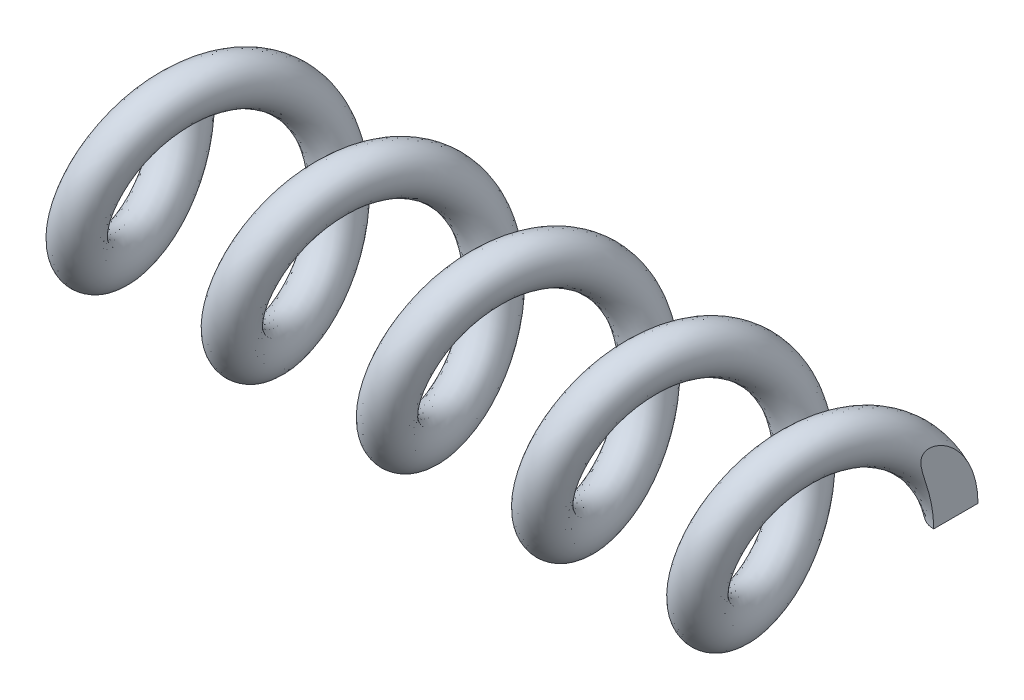
SolidWorks part; units mm, degrees
ref_plane "Front Plane" through (0, 0, 0) normal (0, 0, 1) x (1, 0, 0)
ref_plane "Top Plane" through (0, 0, 0) normal (0, 1, 0) x (1, 0, 0)
ref_plane "Right Plane" through (0, 0, 0) normal (1, 0, 0) x (0, 0, -1)
sketch "Sketch1" plane through (0, 0, 0) normal (1, 0, 0) x (0, 0, -1)
  circle A0 centre (0, 0) radius 4
curve "Helix/Spiral1" pitch 7 height 35 turns 5
sketch "Sketch2" plane through (0, 0, 0) normal (0, 1, 0) x (1, 0, 0)
  line L0 (0, 0) -> (0, 4) construction
  circle A0 centre (0, 4) radius 1
  spline S0 degree 3 poles (261.2112, -1978.3412) (-16.256, -247.6448) (-7.1711, 19.2828) (0.8749, 2.9021) (1.3125, 1.5706) (1.75, 0) (2.1875, -1.5706) (2.625, -2.9021) (3.0625, -3.7917) (3.5, -4.1041) (3.9375, -3.7917) (4.375, -2.9021) (4.8125, -1.5706) (5.25, 0) (5.6875, 1.5706) (6.125, 2.9021) (6.5625, 3.7917) (7, 4.1041) (7.4375, 3.7917) (7.875, 2.9021) (8.3125, 1.5706) (8.75, 0) (9.1875, -1.5706) (9.625, -2.9021) (10.0625, -3.7917) (10.5, -4.1041) (10.9375, -3.7917) (11.375, -2.9021) (11.8125, -1.5706) (12.25, 0) (12.6875, 1.5706) (13.125, 2.9021) (13.5625, 3.7917) (14, 4.1041) (14.4375, 3.7917) (14.875, 2.9021) (15.3125, 1.5706) (15.75, 0) (16.1875, -1.5706) (16.625, -2.9021) (17.0625, -3.7917) (17.5, -4.1041) (17.9375, -3.7917) (18.375, -2.9021) (18.8125, -1.5706) (19.25, 0) (19.6875, 1.5706) (20.125, 2.9021) (20.5625, 3.7917) (21, 4.1041) (21.4375, 3.7917) (21.875, 2.9021) (22.3125, 1.5706) (22.75, 0) (23.1875, -1.5706) (23.625, -2.9021) (24.0625, -3.7917) (24.5, -4.1041) (24.9375, -3.7917) (25.375, -2.9021) (25.8125, -1.5706) (26.25, 0) (26.6875, 1.5706) (27.125, 2.9021) (27.5625, 3.7917) (28, 4.1041) (28.4375, 3.7917) (28.875, 2.9021) (29.3125, 1.5706) (29.75, 0) (30.1875, -1.5706) (30.625, -2.9021) (31.0625, -3.7917) (31.5, -4.1041) (31.9375, -3.7917) (32.375, -2.9021) (32.8125, -1.5706) (33.25, 0) (33.6875, 1.5706) (34.1251, 2.9021) (42.1711, 19.2829) (51.2562, -247.65) (-226.2194, -1978.392) knots -0.652959 -0.652959 -0.652959 -0.652959 0.0125 0.025 0.0375 0.05 0.0625 0.075 0.0875 0.1 0.1125 0.125 0.1375 0.15 0.1625 0.175 0.1875 0.2 0.2125 0.225 0.2375 0.25 0.2625 0.275 0.2875 0.3 0.3125 0.325 0.3375 0.35 0.3625 0.375 0.3875 0.4 0.4125 0.425 0.4375 0.45 0.4625 0.475 0.4875 0.5 0.5125 0.525 0.5375 0.55 0.5625 0.575 0.5875 0.6 0.6125 0.625 0.6375 0.65 0.6625 0.675 0.6875 0.7 0.7125 0.725 0.7375 0.75 0.7625 0.775 0.7875 0.8 0.8125 0.825 0.8375 0.85 0.8625 0.875 0.8875 0.9 0.9125 0.925 0.9375 0.95 0.9625 0.975 0.9875 1.652966 1.652966 1.652966 1.652966 only from (0, 4) to (35, 4) construction
  spline S1 degree 3 poles (0, 4) (0.145, 4) (0.4379, 3.7917) (0.8749, 2.9021) (1.3125, 1.5706) (1.75, 0) (2.1875, -1.5706) (2.625, -2.9021) (3.0625, -3.7917) (3.5, -4.1041) (3.9375, -3.7917) (4.375, -2.9021) (4.8125, -1.5706) (5.25, 0) (5.6875, 1.5706) (6.125, 2.9021) (6.5625, 3.7917) (7, 4.1041) (7.4375, 3.7917) (7.875, 2.9021) (8.3125, 1.5706) (8.75, 0) (9.1875, -1.5706) (9.625, -2.9021) (10.0625, -3.7917) (10.5, -4.1041) (10.9375, -3.7917) (11.375, -2.9021) (11.8125, -1.5706) (12.25, 0) (12.6875, 1.5706) (13.125, 2.9021) (13.5625, 3.7917) (14, 4.1041) (14.4375, 3.7917) (14.875, 2.9021) (15.3125, 1.5706) (15.75, 0) (16.1875, -1.5706) (16.625, -2.9021) (17.0625, -3.7917) (17.5, -4.1041) (17.9375, -3.7917) (18.375, -2.9021) (18.8125, -1.5706) (19.25, 0) (19.6875, 1.5706) (20.125, 2.9021) (20.5625, 3.7917) (21, 4.1041) (21.4375, 3.7917) (21.875, 2.9021) (22.3125, 1.5706) (22.75, 0) (23.1875, -1.5706) (23.625, -2.9021) (24.0625, -3.7917) (24.5, -4.1041) (24.9375, -3.7917) (25.375, -2.9021) (25.8125, -1.5706) (26.25, 0) (26.6875, 1.5706) (27.125, 2.9021) (27.5625, 3.7917) (28, 4.1041) (28.4375, 3.7917) (28.875, 2.9021) (29.3125, 1.5706) (29.75, 0) (30.1875, -1.5706) (30.625, -2.9021) (31.0625, -3.7917) (31.5, -4.1041) (31.9375, -3.7917) (32.375, -2.9021) (32.8125, -1.5706) (33.25, 0) (33.6875, 1.5706) (34.1251, 2.9021) (34.5621, 3.7917) (34.855, 4) (35, 4) knots 0 0 0 0 0.0125 0.025 0.0375 0.05 0.0625 0.075 0.0875 0.1 0.1125 0.125 0.1375 0.15 0.1625 0.175 0.1875 0.2 0.2125 0.225 0.2375 0.25 0.2625 0.275 0.2875 0.3 0.3125 0.325 0.3375 0.35 0.3625 0.375 0.3875 0.4 0.4125 0.425 0.4375 0.45 0.4625 0.475 0.4875 0.5 0.5125 0.525 0.5375 0.55 0.5625 0.575 0.5875 0.6 0.6125 0.625 0.6375 0.65 0.6625 0.675 0.6875 0.7 0.7125 0.725 0.7375 0.75 0.7625 0.775 0.7875 0.8 0.8125 0.825 0.8375 0.85 0.8625 0.875 0.8875 0.9 0.9125 0.925 0.9375 0.95 0.9625 0.975 0.9875 1 1 1 1
sweep "Sweep1" add profiles "Sketch2" path "Helix/Spiral1"
sketch "Sketch3" plane through (0, 0, 0) normal (0, 1, 0) x (1, 0, 0)
  line L0 (0, 4) -> (0, 5) construction
  line L2 (0, 5) -> (-5.8821, 5)
  line L3 (0, 5) -> (0, -6.5178)
  line L4 (0, -6.5178) -> (-5.8821, -6.5178)
  line L5 (-5.8821, 5) -> (-5.8821, -6.5178)
  circle A0 centre (0, 4) radius 1 construction
extrude "Cut-Extrude1" cut sketch "Sketch3" against normal blind 10
sketch "Sketch4" plane through (0, 0, 0) normal (0, -1, 0) x (1, 0, 0)
  line L1 (35, -5) -> (38.2612, -5)
  line L2 (35, -5) -> (35, 2.0401)
  line L3 (35, 2.0401) -> (38.2612, 2.0401)
  line L4 (38.2612, -5) -> (38.2612, 2.0401)
  circle A0 centre (35, -4) radius 1 construction
extrude "Cut-Extrude2" cut sketch "Sketch4" against normal blind 10 contours L4 L3 L2 L1
